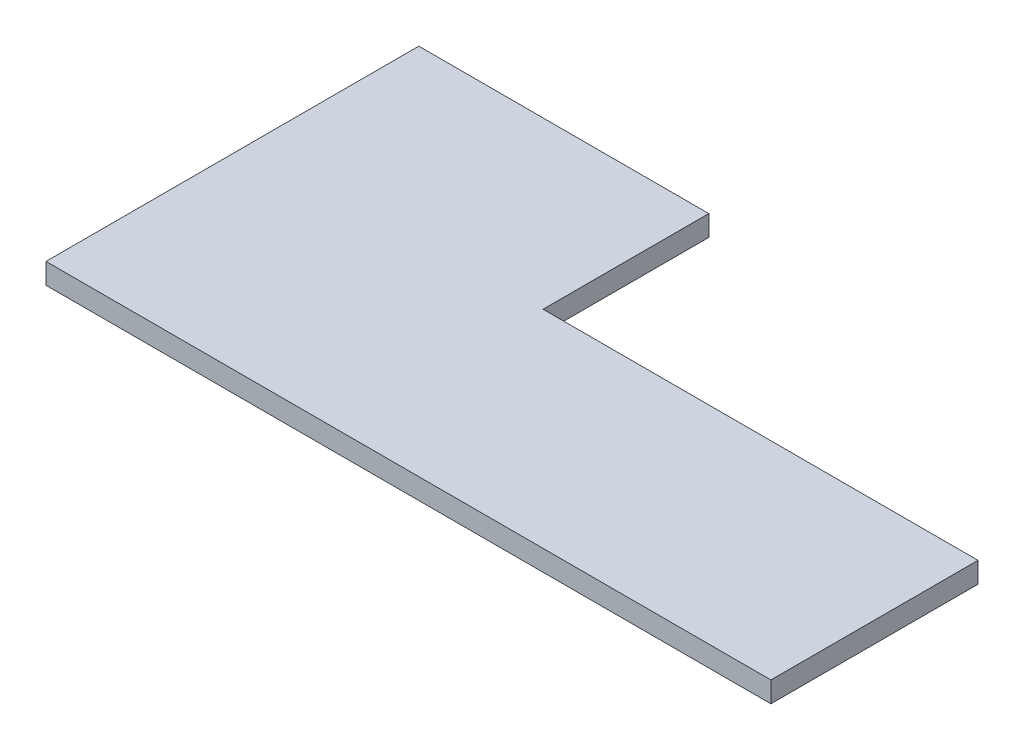
SolidWorks part; units mm, degrees
ref_plane "Ebene vorne" through (0, 0, 0) normal (0, 0, 1) x (1, 0, 0)
ref_plane "Ebene oben" through (0, 0, 0) normal (0, 1, 0) x (1, 0, 0)
ref_plane "Ebene rechts" through (0, 0, 0) normal (1, 0, 0) x (0, 0, -1)
sketch "Sketch1" plane through (0, 0, 0) normal (0, 1, 0) x (1, 0, 0)
  line L1 (0, 0) -> (35, 0)
  line L2 (0, 0) -> (0, 18)
  line L3 (0, 18) -> (35, 18)
  line L4 (35, 0) -> (35, 18)
  line L5 (35, 18) -> (14, 18)
  line L6 (35, 18) -> (35, 10)
  line L7 (35, 10) -> (14, 10)
  line L8 (14, 18) -> (14, 10)
  dimension "D1" = 18
  dimension "D2" = 35
  dimension "D3" = 10
  dimension "D4" = 14
extrude "Extrude1" add sketch "Sketch1" along normal blind 1 contours L8 L3 L2 L1 L4 L7
